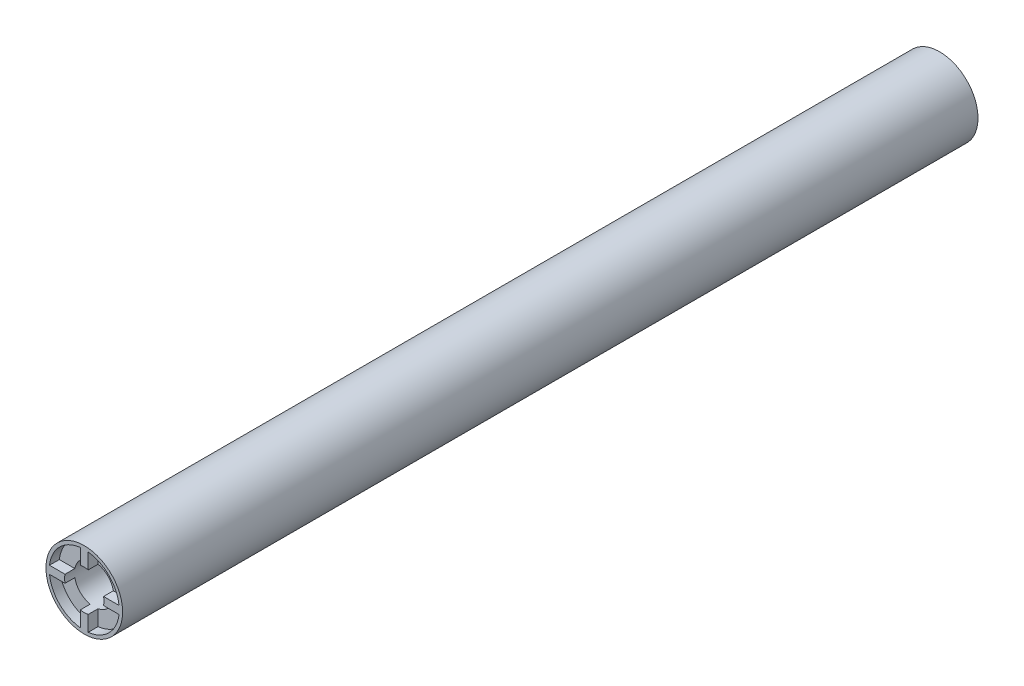
SolidWorks part; units mm, degrees
material "1.8901 (S460N)"
ref_plane "前视基准面" through (0, 0, 0) normal (0, 0, 1) x (1, 0, 0)
ref_plane "上视基准面" through (0, 0, 0) normal (0, 1, 0) x (1, 0, 0)
ref_plane "右视基准面" through (0, 0, 0) normal (1, 0, 0) x (0, 0, -1)
sketch "草图1" plane through (0, 0, 0) normal (0, 0, 1) x (1, 0, 0)
  circle A0 centre (0, 0) radius 1.95
  dimension "D1" = 3.9
extrude "凸台-拉伸1" add sketch "草图1" against normal blind 43
sketch "草图2" plane through (0, 0, -43) normal (0, 0, -1) x (-1, 0, 0)
  circle A0 centre (0, 0) radius 1.95
sketch "草图3" plane through (0, 0, 0) normal (0, 0, 1) x (1, 0, 0)
  circle A0 centre (0, 0) radius 1
  dimension "D1" = 2
extrude "切除-拉伸1" cut sketch "草图3" against normal blind 8
sketch "草图4" plane through (0, 0, 0) normal (0, 0, 1) x (1, 0, 0)
  line L0 (0, 1.95) -> (0, -1.95) construction
  line L1 (-1.95, 0) -> (1.95, 0) construction
  line L2 (-1.9397, 0.2) -> (-0.9798, 0.2)
  line L3 (-1.9397, -0.2) -> (-0.9798, -0.2)
  line L4 (-0.2, 1.9397) -> (-0.2, 0.9798)
  line L5 (0.2, 1.9397) -> (0.2, 0.9798)
  line L6 (0.9798, 0.2) -> (1.9397, 0.2)
  line L7 (0.9798, -0.2) -> (1.9397, -0.2)
  line L10 (-0.2, -0.9798) -> (-0.2, -1.9397)
  line L11 (0.2, -0.9798) -> (0.2, -1.9397)
  circle A0 centre (0, 0) radius 1.95
  circle A1 centre (0, 0) radius 1.78
  circle A2 centre (0, 0) radius 1
  circle M10 centre (0, 0) radius 1
  circle M11 centre (0, 0) radius 1.95
  dimension "D1" = 2
  dimension "D2" = 3.9
  dimension "D3" = 3.56
  dimension "D4" = 0.2
  dimension "D5" = 0.2
  dimension "D6" = 0.2
  dimension "D7" = 0.2
extrude "凸台-拉伸3" add sketch "草图4" along normal blind 0.5 contours A1 L2 L3 M11 | A1 L7 L6 M11 | A1 L11 L7 M11 | A1 L10 L11 M11 | A1 L3 L10 M11 | A1 L4 L2 M11 | A1 L6 L5 M11 | A1 L5 L4 M11 | L2 A1 L3 M10 | L7 A1 L6 M10 | L5 A1 L4 M10 | L10 A1 L11 M10
